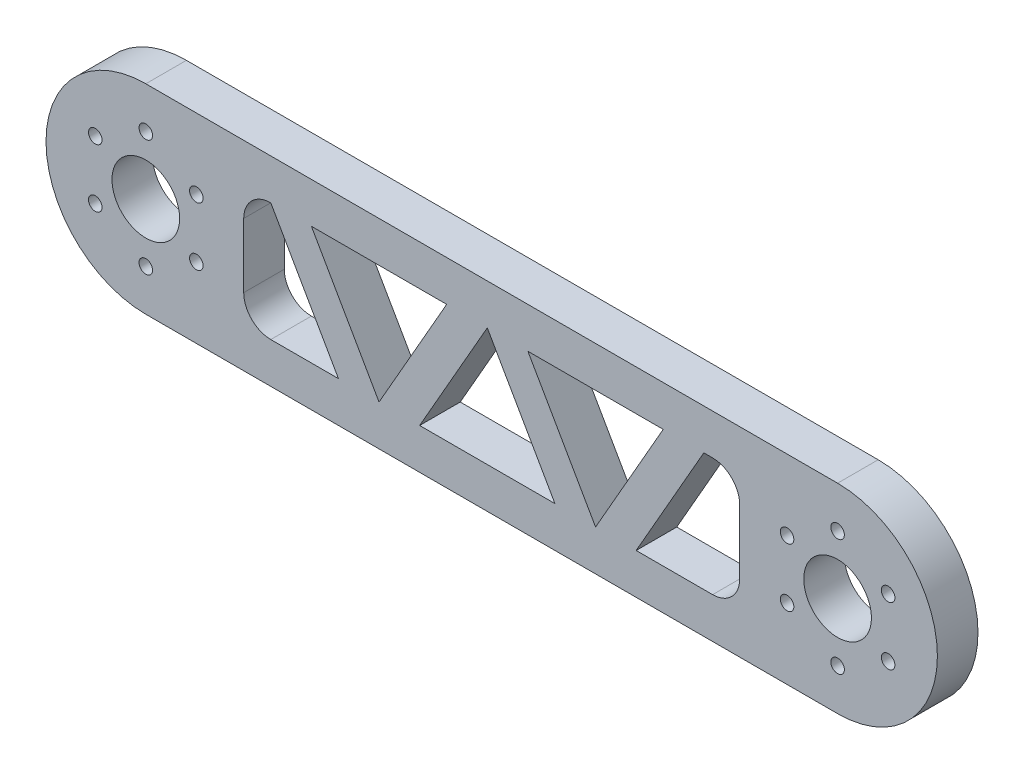
SolidWorks part; units mm, degrees
ref_plane "Front Plane" through (0, 0, 0) normal (0, 0, 1) x (1, 0, 0)
ref_plane "Top Plane" through (0, 0, 0) normal (0, 1, 0) x (1, 0, 0)
ref_plane "Right Plane" through (0, 0, 0) normal (1, 0, 0) x (0, 0, -1)
sketch "Sketch1" plane through (0, 0, 0) normal (0, 0, 1) x (1, 0, 0)
  line L0 (0, 0) -> (204.48, 0) construction
  line L1 (0, 29.5) -> (204.48, 29.5)
  line L2 (0, -29.5) -> (204.48, -29.5)
  arc A0 (0, 29.5) -> (0, -29.5) centre (0, 0) ccw
  arc A1 (204.48, -29.5) -> (204.48, 29.5) centre (204.48, 0) ccw
  point P3 (102.24, 0)
extrude "Boss-Extrude2" add sketch "Sketch1" against normal blind 12 contours L1 A1 L2 A0
sketch "Sketch2" plane through (0, 0, 0) normal (0, 0, 1) x (1, 0, 0)
  circle A0 centre (0, 17.25) radius 2
  dimension "D1" = 17.25
extrude "Cut-Extrude1" cut sketch "Sketch2" against normal blind 12
pattern_circular "CirPattern1" count 6 every 60 about axis through (0, 0, 0) along (0, 0, 1) of "Cut-Extrude1"
sketch "Sketch4" plane through (0, 0, 0) normal (0, 0, 1) x (1, 0, 0)
  circle A0 centre (204.48, 17.25) radius 2
  circle A1 centre (0, 17.25) radius 2 construction
  dimension "D1" = 0
  dimension "D2" = 0
extrude "Cut-Extrude2" cut sketch "Sketch4" against normal blind 12 contours A0
pattern_circular "CirPattern2" count 6 every 60 about axis through (204.48, 0, 0) along (0, 0, 1) of "Cut-Extrude2"
sketch "Sketch7" plane through (0, 0, 0) normal (0, 0, 1) x (1, 0, 0)
  line L0 (0, 29.5) -> (204.48, 29.5) construction
  line L1 (36.9389, 17.5) -> (167.5411, 17.5)
  line L2 (28.9389, 9.5) -> (28.9389, -9.5)
  line L3 (36.9389, -17.5) -> (167.5411, -17.5)
  line L4 (175.5411, 9.5) -> (175.5411, -9.5)
  line L5 (0, -29.5) -> (204.48, -29.5) construction
  line L6 (36.9389, 17.5) -> (48.9389, 17.5)
  line L7 (36.9389, 17.5) -> (56.9389, -17.5)
  line L8 (48.9389, 17.5) -> (68.9389, -17.5)
  line L9 (56.9389, -17.5) -> (68.9389, -17.5)
  line L10 (68.9389, -17.5) -> (80.9389, -17.5)
  line L11 (68.9389, -17.5) -> (88.9389, 17.5)
  line L12 (80.9389, -17.5) -> (100.9389, 17.5)
  line L13 (88.9389, 17.5) -> (100.9389, 17.5)
  line L14 (100.9389, 17.5) -> (112.9389, 17.5)
  line L15 (100.9389, 17.5) -> (120.9389, -17.5)
  line L16 (112.9389, 17.5) -> (132.9389, -17.5)
  line L17 (120.9389, -17.5) -> (132.9389, -17.5)
  line L18 (132.9389, -17.5) -> (144.9389, -17.5)
  line L19 (132.9389, -17.5) -> (152.9389, 17.5)
  line L20 (144.9389, -17.5) -> (164.9389, 17.5)
  line L21 (152.9389, 17.5) -> (164.9389, 17.5)
  circle A0 centre (14.9389, -8.625) radius 2 construction
  circle A1 centre (189.5411, -8.625) radius 2 construction
  arc A2 (36.9389, 17.5) -> (28.9389, 9.5) centre (36.9389, 9.5) ccw
  arc A3 (28.9389, -9.5) -> (36.9389, -17.5) centre (36.9389, -9.5) ccw
  arc A4 (167.5411, -17.5) -> (175.5411, -9.5) centre (167.5411, -9.5) ccw
  arc A5 (167.5411, 17.5) -> (175.5411, 9.5) centre (167.5411, 9.5) cw
  point P16 (28.9389, 17.5)
  point P19 (28.9389, -17.5)
  dimension "D3" = 14
  dimension "D5" = 8
  dimension "D1" = 12
  dimension "D2" = 12
  dimension "D4" = 14
  dimension "D6" = 12
  dimension "D7" = 20
  dimension "D8" = 12
  dimension "D9" = 20
  dimension "D10" = 12
  dimension "D11" = 20
  dimension "D12" = 12
  dimension "D13" = 20
extrude "Cut-Extrude4" cut sketch "Sketch7" against normal blind 12 contours L2 A3 L3 L7 A2 | L8 L11 L1 | L15 L12 L3 | L16 L19 L1 | A5 L1 L20 L3 A4 L4
sketch "Sketch8" plane through (0, 0, 0) normal (0, 0, 1) x (1, 0, 0)
  circle A0 centre (0, 0) radius 10
sketch "Sketch9" plane through (0, 0, 0) normal (0, 0, 1) x (1, 0, 0)
  circle A0 centre (204.48, 0) radius 10
extrude "Cut-Extrude5" cut sketch "Sketch8" against normal blind 12 contours A0
extrude "Cut-Extrude6" cut sketch "Sketch9" against normal blind 12 contours A0
sketch "Sketch10" plane through (0, 0, -12) normal (0, 0, -1) x (-1, 0, 0)
  circle A0 centre (-204.48, 17.25) radius 3.75
extrude "Cut-Extrude7" cut sketch "Sketch10" against normal blind 6 contours A0
pattern_circular "CirPattern3" count 6 every 60 about axis through (204.48, 0, 0) along (0, 0, 1) of "Cut-Extrude7"
sketch "Sketch11" plane through (0, 0, -12) normal (0, 0, -1) x (-1, 0, 0)
  circle A0 centre (0, 17.25) radius 3.75
extrude "Cut-Extrude8" cut sketch "Sketch11" against normal blind 6 contours A0
pattern_circular "CirPattern4" count 6 every 60 about axis through (0, 0, 0) along (0, 0, 1) of "Cut-Extrude8"
